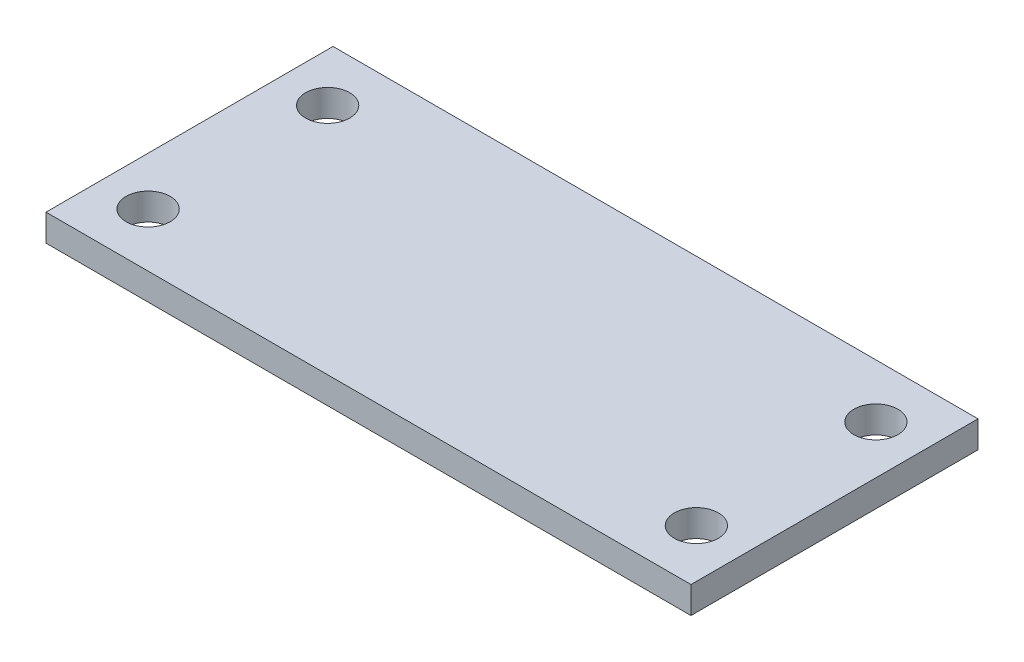
SolidWorks part; units mm, degrees
ref_plane "Plan de face" through (0, 0, 0) normal (0, 0, 1) x (1, 0, 0)
ref_plane "Plan de dessus" through (0, 0, 0) normal (0, 1, 0) x (1, 0, 0)
ref_plane "Plan de droite" through (0, 0, 0) normal (1, 0, 0) x (0, 0, -1)
sketch "Esquisse1" plane through (0, 0, 0) normal (0, 1, 0) x (1, 0, 0)
  line L0 (0, 46.2655) -> (0, -40.4028) construction
  line L1 (-30, 13.35) -> (30, 13.35)
  line L2 (-30, 13.35) -> (-30, -13.35)
  line L3 (-30, -13.35) -> (30, -13.35)
  line L4 (30, 13.35) -> (30, -13.35)
  line L5 (-30, 13.35) -> (30, -13.35) construction
  line L6 (-30, -13.35) -> (30, 13.35) construction
  line L7 (-45.7875, 0) -> (63.1442, 0) construction
  circle A0 centre (-25.5, 8.35) radius 2.05
  circle A1 centre (25.5, 8.35) radius 2.05
  circle A2 centre (25.5, -8.35) radius 2.05
  circle A3 centre (-25.5, -8.35) radius 2.05
  point P0 (0, 0)
  dimension "D3" = 5
  dimension "D4" = 4.1
  dimension "D1" = 60
  dimension "D2" = 26.7
  dimension "D5" = 51
extrude "Boss.-Extru.1" add sketch "Esquisse1" along normal blind 2.5
